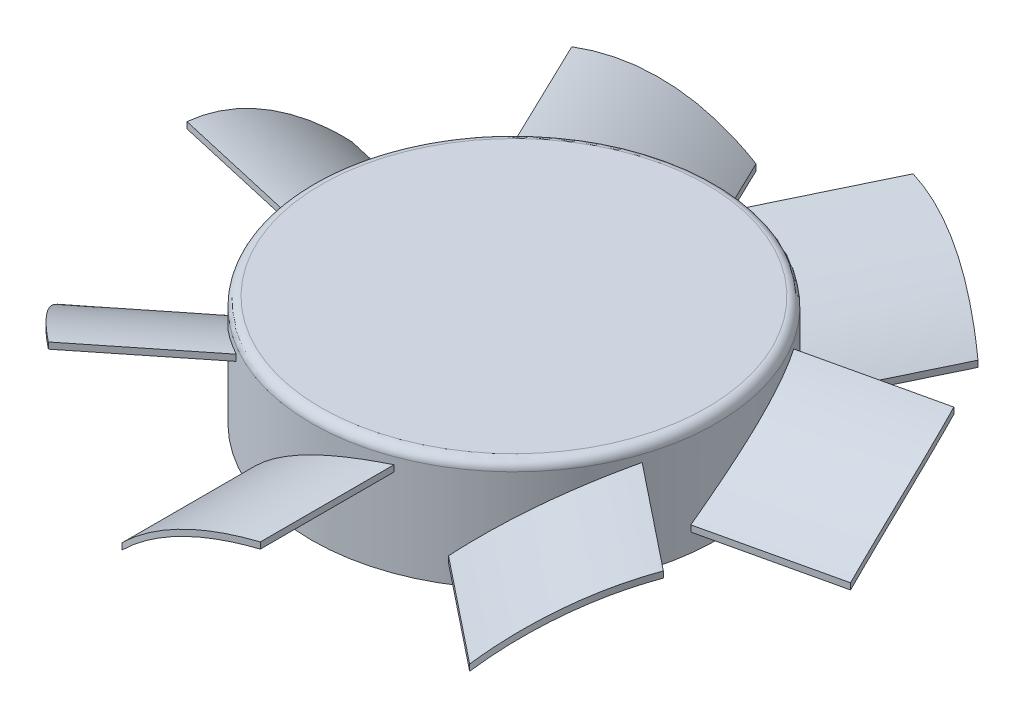
SolidWorks part; units mm, degrees
ref_plane "Спереди" through (0, 0, 0) normal (0, 0, 1) x (1, 0, 0)
ref_plane "Сверху" through (0, 0, 0) normal (0, 1, 0) x (1, 0, 0)
ref_plane "Справа" through (0, 0, 0) normal (1, 0, 0) x (0, 0, -1)
sketch "Эскиз1" plane through (0, 0, 0) normal (0, 1, 0) x (1, 0, 0)
  circle A0 centre (0, 0) radius 11
  dimension "D1" = 22
extrude "Бобышка-Вытянуть1" add sketch "Эскиз1" along normal blind 6
sketch "Эскиз3" plane through (0, 0, 0) normal (0, 0, 1) x (1, 0, 0)
  line L2 (-3.7, 1.34) -> (-3.7, 1)
  line L3 (3.8, 5.12) -> (3.8, 4.78)
  spline S0 degree 3 poles (3.8, 5.12) (0.9316, 4.8732) (-1.6897, 3.3321) (-3.7, 1.34) knots 0 0 0 0 1 1 1 1
  spline S1 degree 3 poles (3.8, 4.78) (0.9316, 4.5332) (-1.6897, 2.9921) (-3.7, 1) knots 0 0 0 0 1 1 1 1
  dimension "D1" = 3.7
  dimension "D2" = 3.8
  dimension "D3" = 1.32
  dimension "D4" = 1.53
  dimension "D5" = 1.34
  dimension "D6" = 3.13
  dimension "D7" = 4.58
  dimension "D8" = 5.12
  dimension "D9" = 3.8
  dimension "D10" = 1.32
  dimension "D11" = 3.7
  dimension "D12" = 1.53
  dimension "D13" = 1
  dimension "D14" = 2.79
  dimension "D15" = 4.24
  dimension "D16" = 4.78
extrude "Бобышка-Вытянуть2" add sketch "Эскиз3" along normal blind 25
pattern_circular "Круговой массив1" count 7 over 360 about axis through (0, 6, 0) along (0, 1, 0) of "Бобышка-Вытянуть2"
sketch "Эскиз4" plane through (0, 6, 0) normal (0, 1, 0) x (1, 0, 0)
  circle A0 centre (0, 0) radius 18
  circle A1 centre (0, 0) radius 35
  dimension "D1" = 36
  dimension "D2" = 70
extrude "Вырез-Вытянуть2" cut sketch "Эскиз4" against normal blind 25
fillet "Скругление1" radius 0.5 1 edges at (0, 6, 11)
sketch "Эскиз2" plane through (0, 0, 0) normal (0, -1, 0) x (1, 0, 0)
  circle A0 centre (0, 0) radius 4.1
  dimension "D1" = 8.2
extrude "Вырез-Вытянуть1" cut sketch "Эскиз2" against normal blind 5
